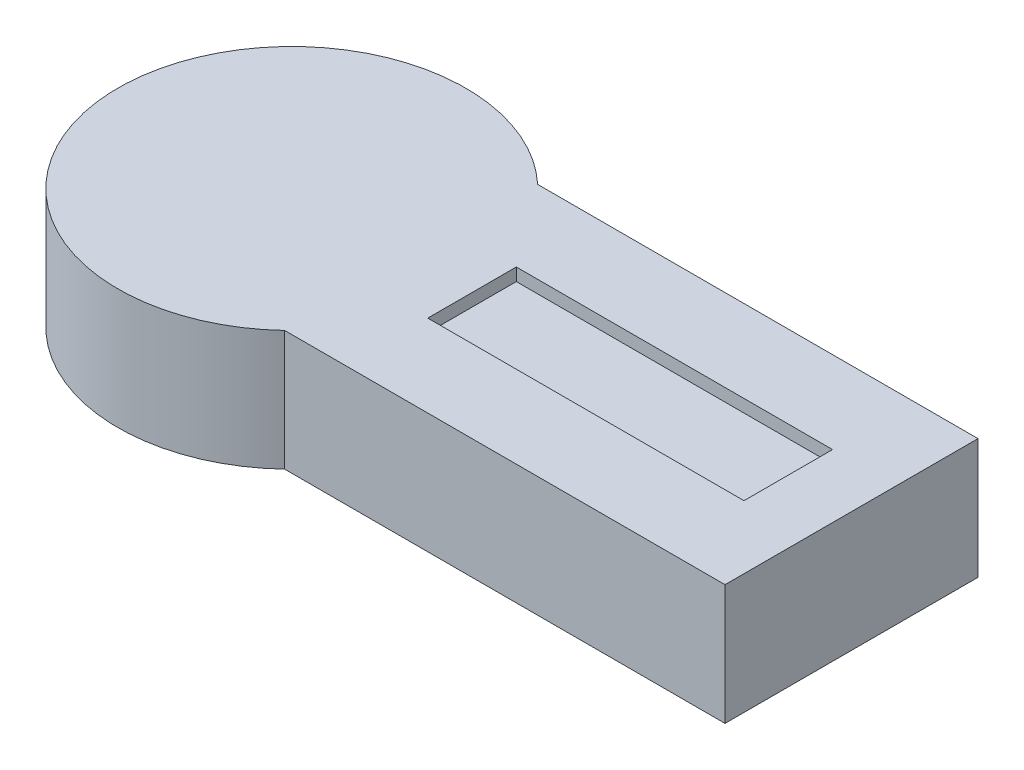
SolidWorks part; units mm, degrees
ref_plane "Front Plane" through (0, 0, 0) normal (0, 0, 1) x (1, 0, 0)
ref_plane "Top Plane" through (0, 0, 0) normal (0, 1, 0) x (1, 0, 0)
ref_plane "Right Plane" through (0, 0, 0) normal (1, 0, 0) x (0, 0, -1)
sketch "Sketch1" plane through (0, 0, 0) normal (0, 1, 0) x (1, 0, 0)
  circle A0 centre (0, 0) radius 13.75
  dimension "D1" = 27.5
extrude "Boss-Extrude1" add sketch "Sketch1" along normal blind 9.5
sketch "Sketch2" plane through (0, 0, 0) normal (0, 1, 0) x (1, 0, 0)
  line L1 (0, 10) -> (44.25, 10)
  line L2 (0, 10) -> (0, -10)
  line L3 (0, -10) -> (44.25, -10)
  line L4 (44.25, 10) -> (44.25, -10)
  dimension "D1" = 20
  dimension "D2" = 44.25
extrude "Boss-Extrude2" add sketch "Sketch2" along normal up to surface (9.5 mm away) contours L1 L4 L3 L2 up to face at (0, 9.5, 13.75)
sketch "Sketch3" plane through (0, 0, 0) normal (1, 0, 0) x (0, 0, -1)
  line L4 (13.75, 0) -> (13.75, 9.5) construction
  line L5 (13.75, 9.5) -> (-13.75, 9.5) construction
  circle A0 centre (0, 4.5) radius 2
  dimension "D1" = 4
  dimension "D2" = 13.75
  dimension "D3" = 5
extrude "Boss-Extrude3" add sketch "Sketch3" against normal offset from surface (16.1265 mm away) 2.5 contours A0
sketch "Sketch4" plane through (0, 9.5, 0) normal (0, 1, 0) x (1, 0, 0)
  line L0 (44.25, 10) -> (44.25, -10) construction
  line L1 (14.25, 3.5) -> (39.25, 3.5)
  line L2 (14.25, 3.5) -> (14.25, -3.5)
  line L3 (14.25, -3.5) -> (39.25, -3.5)
  line L4 (39.25, 3.5) -> (39.25, -3.5)
  line L5 (9.4373, -10) -> (44.25, -10) construction
  dimension "D1" = 7
  dimension "D2" = 25
  dimension "D3" = 5
  dimension "D4" = 6.5
extrude "Cut-Extrude1" cut sketch "Sketch4" against normal blind 1 contours L1 L4 L3 L2
